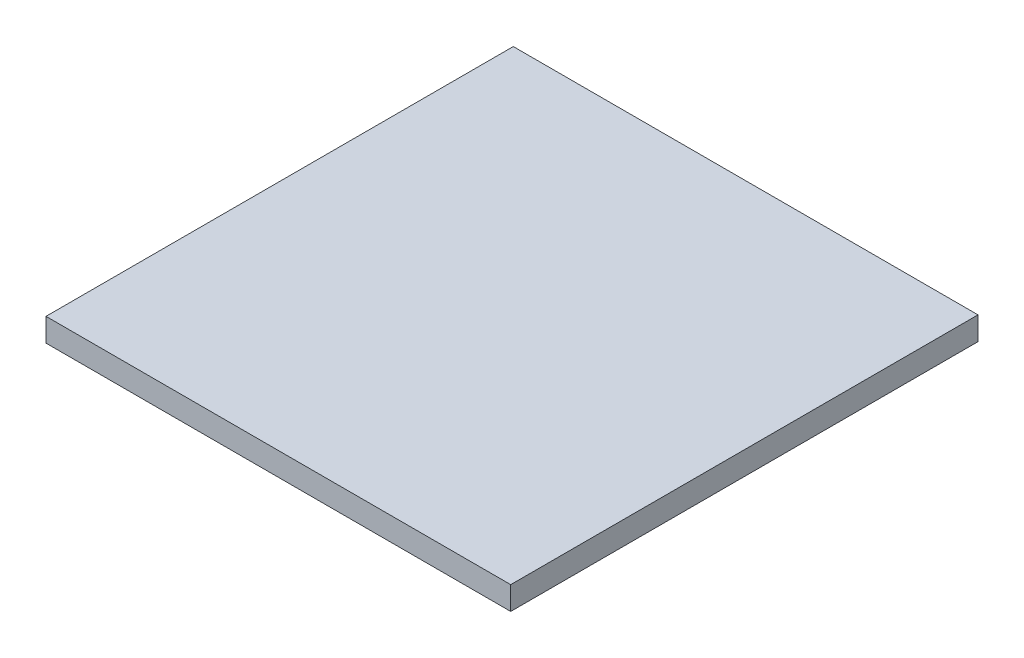
SolidWorks part; units mm, degrees
ref_plane "Alzado" through (0, 0, 0) normal (0, 0, 1) x (1, 0, 0)
ref_plane "Planta" through (0, 0, 0) normal (0, 1, 0) x (1, 0, 0)
ref_plane "Vista lateral" through (0, 0, 0) normal (1, 0, 0) x (0, 0, -1)
sketch "Croquis1" plane through (0, 0, 0) normal (0, 1, 0) x (1, 0, 0)
  line L1 (-180, 181) -> (180, 181)
  line L2 (-180, 181) -> (-180, -181)
  line L3 (-180, -181) -> (180, -181)
  line L4 (180, 181) -> (180, -181)
  line L5 (-180, 181) -> (180, -181) construction
  line L6 (-180, -181) -> (180, 181) construction
  point P0 (0, 0)
  dimension "D1" = 360
  dimension "D2" = 362
extrude "Saliente-Extruir1" add sketch "Croquis1" along normal blind 18
